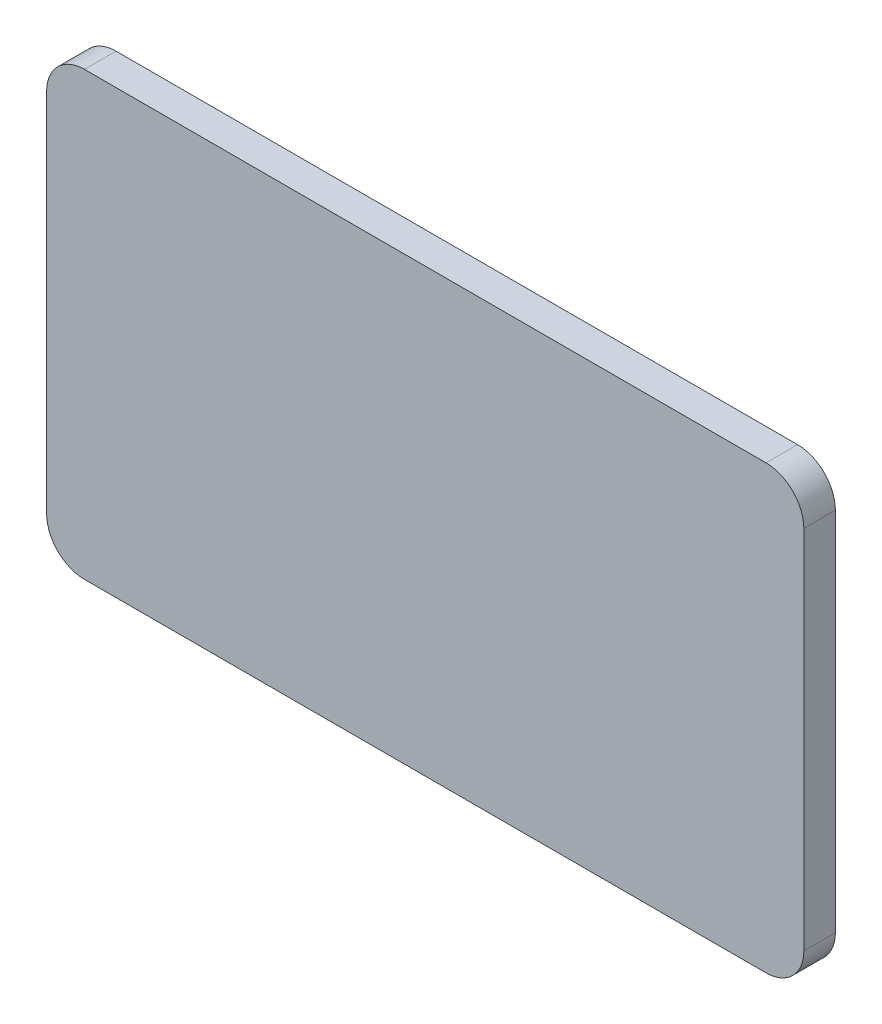
SolidWorks part; units mm, degrees
ref_plane "Front" through (0, 0, 0) normal (0, 0, 1) x (1, 0, 0)
ref_plane "Top" through (0, 0, 0) normal (0, 1, 0) x (1, 0, 0)
ref_plane "Right" through (0, 0, 0) normal (1, 0, 0) x (0, 0, -1)
sketch "Sketch1" plane through (0, 0, 0) normal (0, 0, 1) x (1, 0, 0)
  line L1 (-27, -17.5) -> (27, -17.5)
  line L2 (-30, -14.5) -> (-30, 14.5)
  line L3 (-27, 17.5) -> (27, 17.5)
  line L4 (30, -14.5) -> (30, 14.5)
  line L5 (-30, -17.5) -> (30, 17.5) construction
  line L6 (-30, 17.5) -> (30, -17.5) construction
  arc A0 (27, -17.5) -> (30, -14.5) centre (27, -14.5) ccw
  arc A1 (-30, 14.5) -> (-27, 17.5) centre (-27, 14.5) cw
  arc A2 (-27, -17.5) -> (-30, -14.5) centre (-27, -14.5) cw
  arc A3 (27, 17.5) -> (30, 14.5) centre (27, 14.5) cw
  point P0 (0, 0)
  dimension "D3" = 3
  dimension "D1" = 35
  dimension "D2" = 60
extrude "Boss-Extrude1" add sketch "Sketch1" along normal blind 2.5
